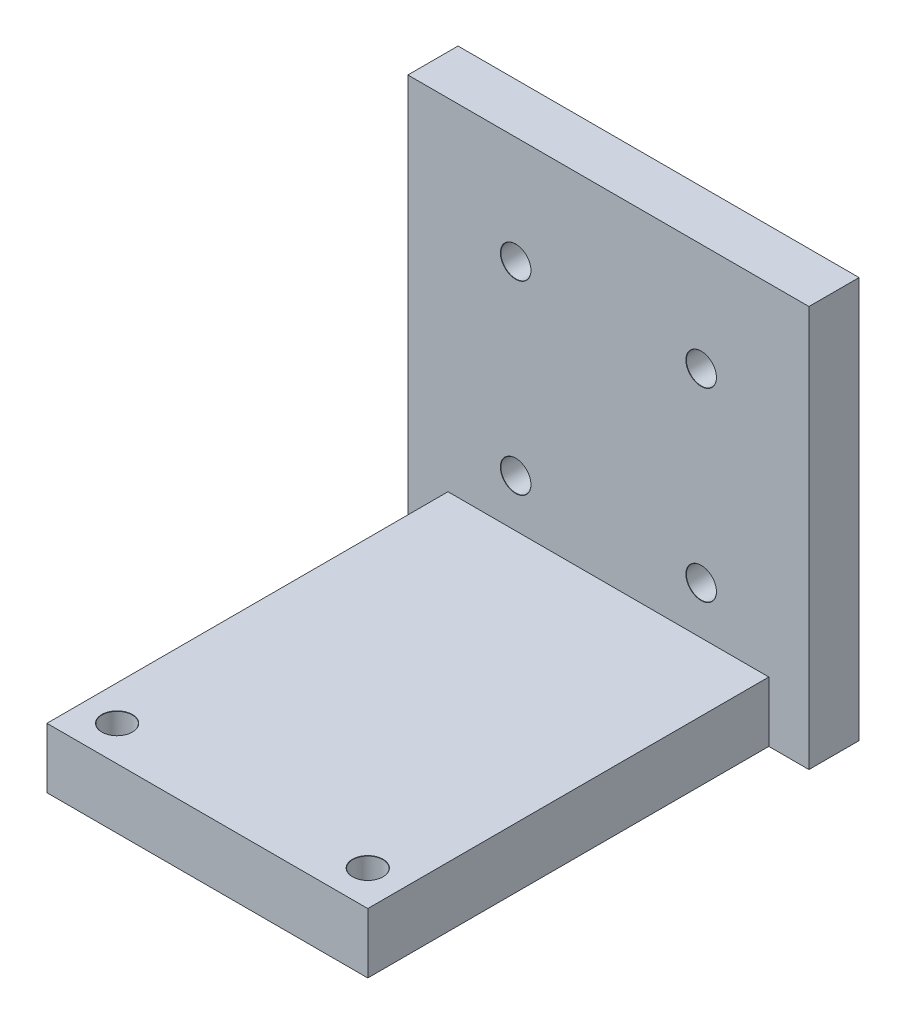
SolidWorks part; units mm, degrees
ref_plane "Płaszczyzna przednia" through (0, 0, 0) normal (0, 0, 1) x (1, 0, 0)
ref_plane "Płaszczyzna górna" through (0, 0, 0) normal (0, 1, 0) x (1, 0, 0)
ref_plane "Płaszczyzna prawa" through (0, 0, 0) normal (1, 0, 0) x (0, 0, -1)
sketch "Szkic1" plane through (0, 0, 0) normal (0, 0, 1) x (1, 0, 0)
  line L1 (0, 0) -> (40, 0)
  line L2 (0, 0) -> (0, 40)
  line L3 (0, 40) -> (40, 40)
  line L4 (40, 0) -> (40, 40)
  dimension "D1" = 40
  dimension "D2" = 40
extrude "Dodanie-wyciągnięcie1" add sketch "Szkic1" along normal blind 5
hole_wizard "Otwory ustalające Ø3.0mm1" positions "Szkic2" profile "Szkic3" hole size "Ø3.0" standard "Ansi Metric" end condition through all
sketch "Szkic2" plane through (0, 0, 5) normal (0, 0, 1) x (1, 0, 0)
  line L0 (0, 40) -> (0, 0) construction
  line L3 (40, 40) -> (0, 40) construction
  line L5 (40, 0) -> (40, 40) construction
  point P0 (10.75, 29.25)
  point P2 (29.25, 29.25)
  point P4 (10.75, 10.75)
  point P6 (29.25, 10.75)
  dimension "D1" = 18.5
  dimension "D2" = 18.5
  dimension "D3" = 18.5
  dimension "D4" = 18.5
  dimension "D5" = 10.75
  dimension "D6" = 10.75
  dimension "D7" = 10.75
sketch "Szkic3" plane through (10.75, 29.25, 5) normal (1, 0, 0) x (0, -1, 0)
  line L0 (0, 0) -> (0, 5)
  line L1 (0, 5) -> (1.5, 5)
  line L2 (1.5, 5) -> (1.5, 0.025)
  line L3 (1.5, 0.025) -> (1.525, 0)
  line L5 (1.525, 0) -> (0, 0)
  line L6 (-1.5, 0.025) -> (-1.525, 0) construction
  line L11 (0, -6.35) -> (0, 107.95) construction
  dimension "Œrednica otworu na wylot" = 3
  dimension "G³êbokoœæ otworu na wylot" = 5
  dimension "Œrednica zewnêtrznego pog³êbienia sto¿kowego" = 3.05
  dimension "K¹t zewnêtrznego pog³êbienia sto¿kowego" = 90
sketch "Szkic4" plane through (0, 0, 5) normal (0, 0, 1) x (1, 0, 0)
  line L0 (0, 0) -> (40, 0) construction
  line L1 (4, 0) -> (36, 0)
  line L2 (4, 0) -> (4, 6)
  line L3 (4, 6) -> (36, 6)
  line L4 (36, 0) -> (36, 6)
  line L5 (0, 40) -> (0, 0) construction
  line L6 (40, 0) -> (40, 40) construction
  dimension "D1" = 6
  dimension "D2" = 4
  dimension "D3" = 4
extrude "Dodanie-wyciągnięcie2" add sketch "Szkic4" along normal blind 40
hole_wizard "Otwory ustalające Ø3.0mm2" positions "Szkic5" profile "Szkic6" hole size "Ø3.0" standard "Ansi Metric" end condition through all
sketch "Szkic5" plane through (0, 6, 0) normal (0, 1, 0) x (1, 0, 0)
  line L0 (4, -45) -> (4, -5) construction
  line L1 (36, -45) -> (36, -5) construction
  line L2 (36, -45) -> (4, -45) construction
  point P0 (7.5, -41.5)
  point P2 (32.5, -41.5)
  point P5 (0, 0)
  dimension "D1" = 3.5
  dimension "D2" = 3.5
  dimension "D3" = 3.5
sketch "Szkic6" plane through (7.5, 6, 41.5) normal (1, 0, 0) x (0, 0, 1)
  line L0 (0, 0) -> (0, 6)
  line L1 (0, 6) -> (1.5, 6)
  line L2 (1.5, 6) -> (1.5, 0.025)
  line L3 (1.5, 0.025) -> (1.525, 0)
  line L5 (1.525, 0) -> (0, 0)
  line L6 (-1.5, 0.025) -> (-1.525, 0) construction
  line L11 (0, -6.35) -> (0, 107.95) construction
  dimension "Œrednica otworu na wylot" = 3
  dimension "G³êbokoœæ otworu na wylot" = 6
  dimension "Œrednica zewnêtrznego pog³êbienia sto¿kowego" = 3.05
  dimension "K¹t zewnêtrznego pog³êbienia sto¿kowego" = 90
